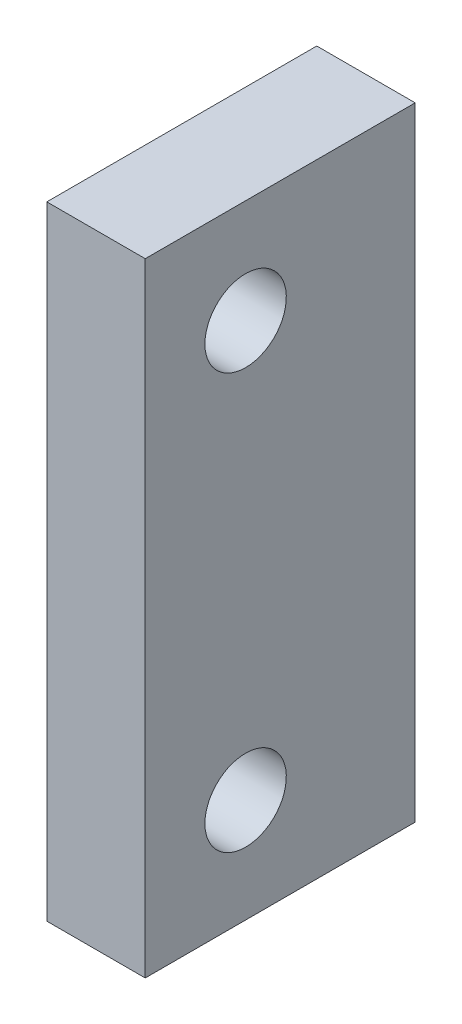
SolidWorks part; units mm, degrees
material "6061 Alloy"
ref_plane "Front Plane" through (0, 0, 0) normal (0, 0, 1) x (1, 0, 0)
ref_plane "Top Plane" through (0, 0, 0) normal (0, 1, 0) x (1, 0, 0)
ref_plane "Right Plane" through (0, 0, 0) normal (1, 0, 0) x (0, 0, -1)
sketch "Sketch2" plane through (-488.9654, 0, 0) normal (1, 0, 0) x (0, 0, -1)
  line L1 (194.9873, 128.4838) -> (194.9873, 166.5838)
  line L2 (194.9873, 126.5338) -> (194.9873, 131.5338) construction
  line L3 (213.8261, 128.4838) -> (175.7261, 128.4838) construction
  line L4 (194.9873, 167.5338) -> (194.9873, 165.7338) construction
  line L5 (175.7261, 166.5838) -> (213.8261, 166.5838) construction
  line L6 (194.9873, 166.5838) -> (178.4773, 166.5838)
  line L7 (178.4773, 166.5838) -> (178.4773, 128.4838)
  line L8 (194.9873, 128.4838) -> (178.4773, 128.4838)
  dimension "D1" = 16.51
extrude "Boss-Extrude1" add sketch "Sketch2" along normal blind 6.0198
hole_wizard "#10 Clearance Hole1" positions "Sketch3" profile "Sketch4" hole size "#10" standard "ANSI Inch"
sketch "Sketch3" plane through (-488.9654, 0, 0) normal (-1, 0, 0) x (0, 0, 1)
  point P0 (-184.6161, 160.2338)
  point P9 (-184.6161, 134.8338)
sketch "Sketch4" plane through (-488.9654, 160.2338, -184.6161) normal (0, 1, 0) x (0, 0, 1)
  line L0 (0, 0) -> (0, 26.8957)
  line L1 (0, 26.8957) -> (2.4892, 25.4)
  line L2 (2.4892, 25.4) -> (2.4892, 0)
  line L5 (2.4892, 0) -> (0, 0)
  line L10 (0, 26.8957) -> (-2.4892, 25.4) construction
  line L11 (0, -6.35) -> (0, 107.95) construction
  dimension "Hole Dia." = 4.9784
  dimension "Hole Depth" = 25.4
  dimension "Drill Angle" = 118
